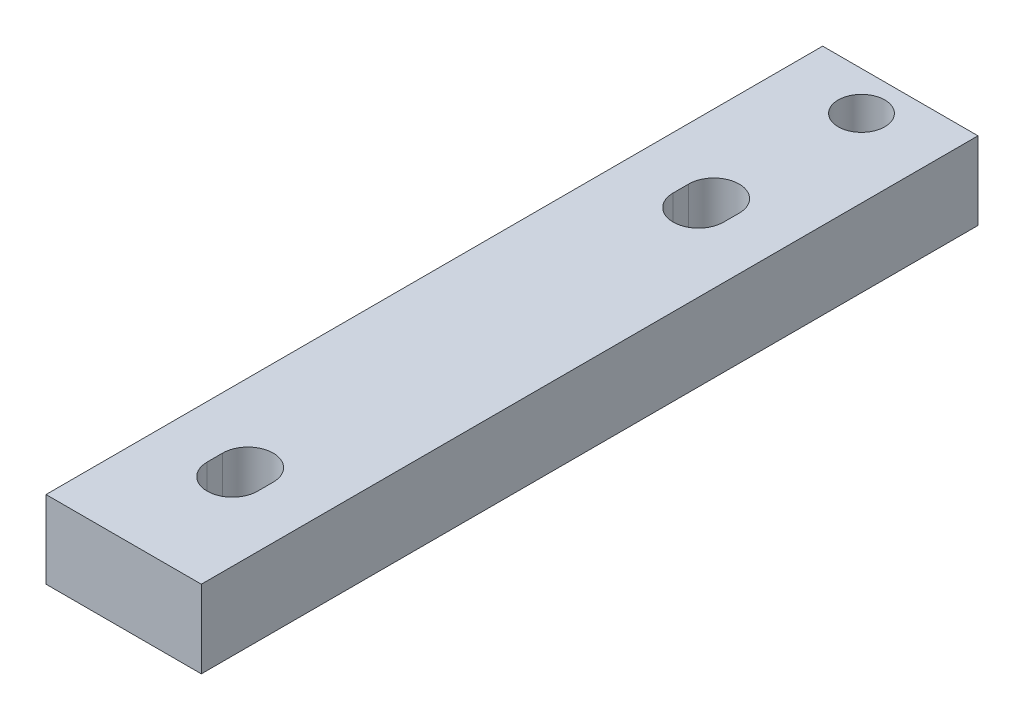
SolidWorks part; units mm, degrees
ref_plane "Front Plane" through (0, 0, 0) normal (0, 0, 1) x (1, 0, 0)
ref_plane "Top Plane" through (0, 0, 0) normal (0, 1, 0) x (1, 0, 0)
ref_plane "Right Plane" through (0, 0, 0) normal (1, 0, 0) x (0, 0, -1)
sketch "Sketch1" plane through (0, 0, 0) normal (0, 1, 0) x (1, 0, 0)
  line L0 (0, 24) -> (0, 26) construction
  line L1 (-10, -50) -> (10, -50)
  line L2 (-10, -50) -> (-10, 50)
  line L3 (-10, 50) -> (10, 50)
  line L4 (10, -50) -> (10, 50)
  line L5 (-10, -50) -> (10, 50) construction
  line L6 (-10, 50) -> (10, -50) construction
  line L7 (-3.25, 24) -> (-3.25, 26)
  line L8 (3.25, 24) -> (3.25, 26)
  line L9 (0, -36) -> (0, -34) construction
  line L10 (-3.25, -36) -> (-3.25, -34)
  line L11 (3.25, -36) -> (3.25, -34)
  line L12 (-10, 40) -> (10, 40) construction
  line L13 (10, 40) -> (10, -50) construction
  line L14 (-10, 40) -> (10, -50) construction
  line L15 (10, 40) -> (-10, -50) construction
  line L16 (0, 25) -> (0, -35) construction
  circle A0 centre (0, 45) radius 3
  arc A4 (-3.25, 24) -> (3.25, 24) centre (0, 24) ccw
  arc A5 (3.25, 26) -> (-3.25, 26) centre (0, 26) ccw
  arc A6 (-3.25, -36) -> (3.25, -36) centre (0, -36) ccw
  arc A7 (3.25, -34) -> (-3.25, -34) centre (0, -34) ccw
  point P0 (0, 0)
  point P10 (0, 25)
  point P16 (0, -35)
  point P26 (0, -5)
  point P27 (0, -5)
  dimension "D3" = 6
  dimension "D6" = 2
  dimension "D1" = 20
  dimension "D2" = 100
  dimension "D4" = 6.5
  dimension "D5" = 5
  dimension "D7" = 60
  dimension "D8" = 10
extrude "Boss-Extrude1" add sketch "Sketch1" along normal blind 10
